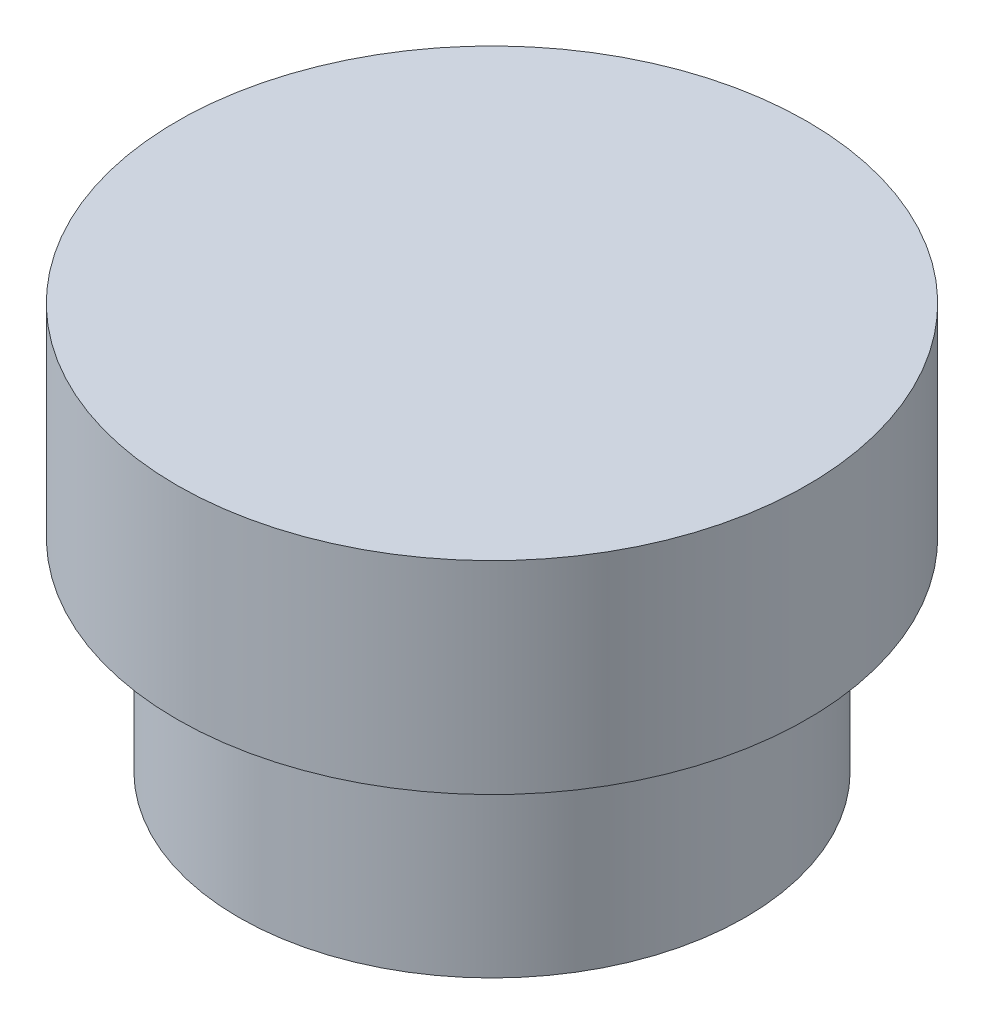
SolidWorks part; units mm, degrees
material "PW80:Mi:0:41:Ar:0:-1:C1:1:2:3:Re:15:"
ref_plane "Plan1" through (0, 0, 0) normal (0, 0, 1) x (1, 0, 0)
ref_plane "Plan2" through (0, 0, 0) normal (0, 1, 0) x (1, 0, 0)
ref_plane "Plan3" through (0, 0, 0) normal (1, 0, 0) x (0, 0, -1)
sketch "Esquisse1" plane through (0, 0, 0) normal (0, 1, 0) x (1, 0, 0)
  circle A0 centre (0, 0) radius 14
extrude "Base-Extrusion" add sketch "Esquisse1" along normal blind 9
sketch "Esquisse2" plane through (0, 0, 0) normal (0, -1, 0) x (1, 0, 0)
  circle A0 centre (0, 0) radius 11.25
extrude "Boss.-Extru.1" add sketch "Esquisse2" along normal blind 9
ref_plane "Plan4" through (0, -9, 0) normal (0, 1, 0) x (-1, 0, 0)
